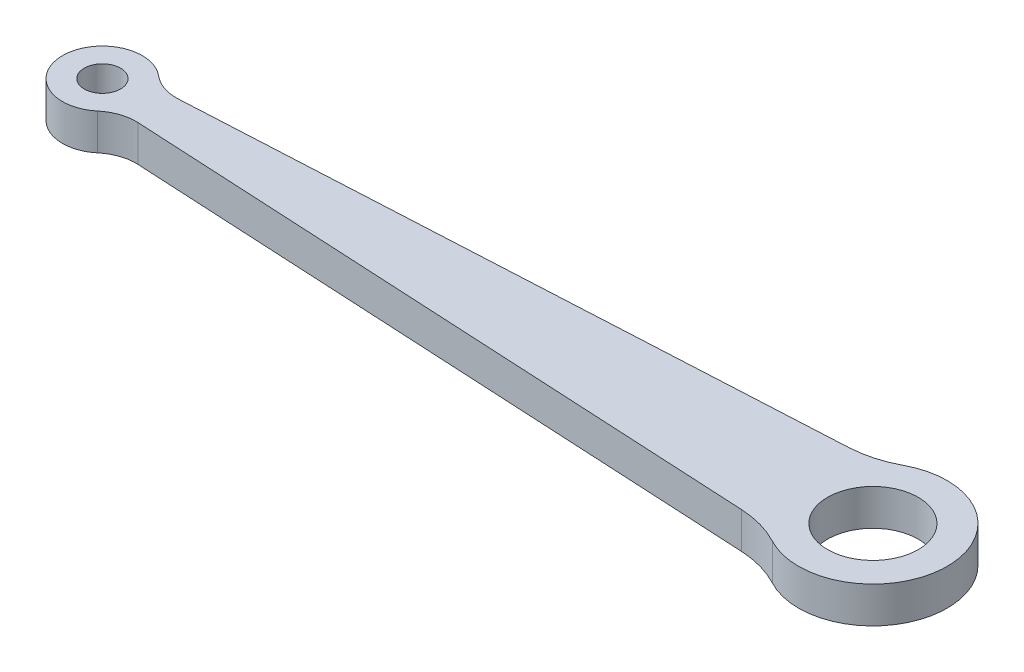
SolidWorks part; units mm, degrees
material "1060 Alloy"
ref_plane "Front Plane" through (0, 0, 0) normal (0, 0, 1) x (1, 0, 0)
ref_plane "Top Plane" through (0, 0, 0) normal (0, 1, 0) x (1, 0, 0)
ref_plane "Right Plane" through (0, 0, 0) normal (1, 0, 0) x (0, 0, -1)
sketch "Sketch1" plane through (0, 0, 0) normal (0, 1, 0) x (1, 0, 0)
  line L0 (0, 0) -> (67.4624, 0) construction
  line L1 (4.9067, 1.778) -> (60.664, 4.7001)
  line L2 (4.9067, -1.778) -> (60.664, -4.7001)
  circle A0 centre (0, 0) radius 1.5875
  arc A1 (2.2513, 2.67) -> (2.2513, -2.67) centre (0, 0) ccw
  circle A2 centre (67.4624, 0) radius 3.9688
  arc A3 (64.3922, -5.7391) -> (64.3922, 5.7391) centre (67.4624, 0) ccw
  arc A4 (60.664, 4.7001) -> (64.3922, 5.7391) centre (60.1987, 13.5779) ccw
  arc A5 (60.664, -4.7001) -> (64.3922, -5.7391) centre (60.1987, -13.5779) cw
  arc A6 (2.2513, 2.67) -> (4.9067, 1.778) centre (4.7073, 5.5828) ccw
  arc A7 (2.2513, -2.67) -> (4.9067, -1.778) centre (4.7073, -5.5828) cw
  dimension "D1" = 3.175
  dimension "D2" = 7.9375
  dimension "D3" = 2.54
  dimension "D4" = 1.905
  dimension "D8" = 8.89
  dimension "D9" = 8.89
  dimension "D6" = 3.81
  dimension "D10" = 3.81
  dimension "D5" = 3
  dimension "D7" = 67.4624
  dimension "D11" = 1.778
  dimension "D12" = 1.778
  dimension "D13" = 3
extrude "Boss-Extrude1" add sketch "Sketch1" along normal blind 3.175
